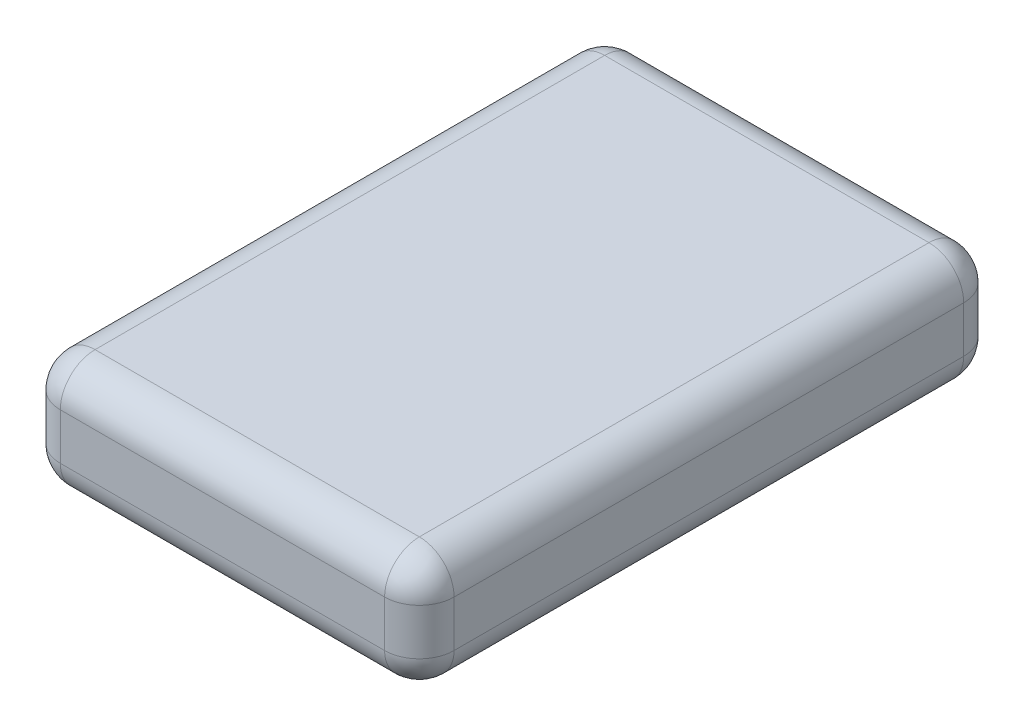
SolidWorks part; units mm, degrees
ref_plane "Front Plane" through (0, 0, 0) normal (0, 0, 1) x (1, 0, 0)
ref_plane "Top Plane" through (0, 0, 0) normal (0, 1, 0) x (1, 0, 0)
ref_plane "Right Plane" through (0, 0, 0) normal (1, 0, 0) x (0, 0, -1)
sketch "Sketch1" plane through (0, 0, 0) normal (0, 1, 0) x (1, 0, 0)
  line L1 (-17, 25) -> (17, 25)
  line L2 (-17, 25) -> (-17, -25)
  line L3 (-17, -25) -> (17, -25)
  line L4 (17, 25) -> (17, -25)
  line L5 (0, -25) -> (0, 25) construction
  line L6 (-17, 0) -> (17, 0) construction
  point P0 (0, 0)
  dimension "D1" = 50
  dimension "D2" = 34
extrude "Boss-Extrude1" add sketch "Sketch1" along normal blind 10
fillet "Fillet1" radius 3 4 edges at (-17, 0, 0) (-17, 10, 0) (17, 0, 0) (17, 10, 0)
fillet "Fillet2" radius 3 16 edges at (-16.1213, 9.1213, 25) (-17, 5, 25) (-16.1213, 0.8787, 25) (0, 0, 25) (16.1213, 0.8787, 25) (17, 5, 25) (16.1213, 9.1213, 25) (16.1213, 9.1213, -25) (17, 5, -25) (16.1213, 0.8787, -25) (0, 0, -25) (-16.1213, 0.8787, -25) (-17, 5, -25) (-16.1213, 9.1213, -25) (0, 10, 25) (0, 10, -25)
